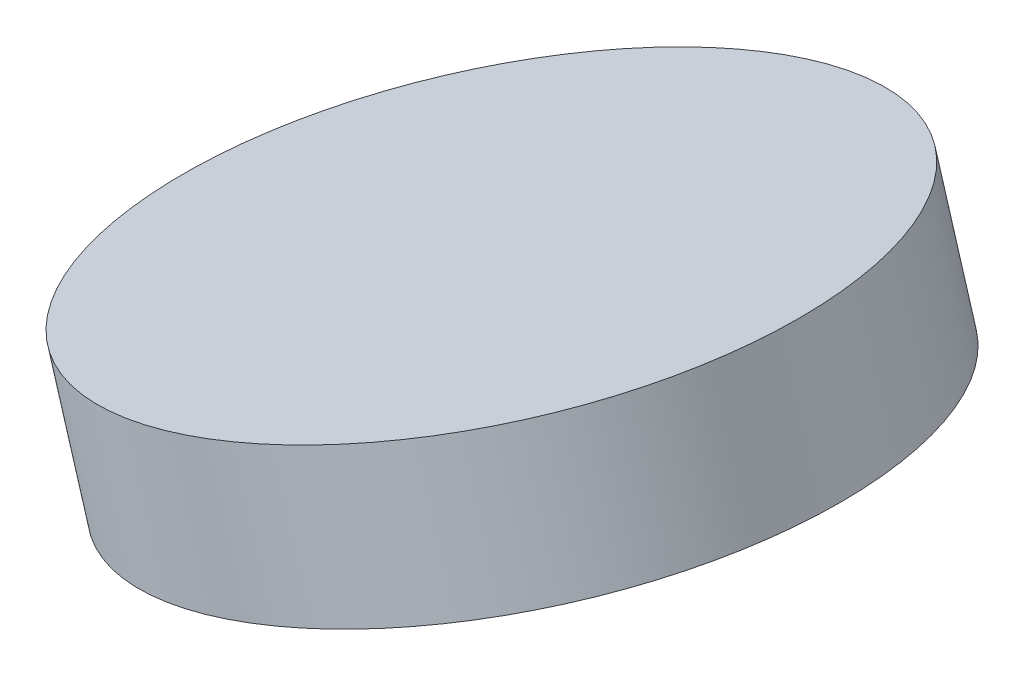
SolidWorks part; units mm, degrees
ref_plane "Front Plane" through (0, 0, 0) normal (0, 0, 1) x (1, 0, 0)
ref_plane "Top Plane" through (0, 0, 0) normal (0, 1, 0) x (1, 0, 0)
ref_plane "Right Plane" through (0, 0, 0) normal (1, 0, 0) x (0, 0, -1)
sketch "Sketch1" plane through (-3.424, 11.5011, 0) normal (0.2853, -0.9584, 0) x (-0.9186, -0.2735, -0.2853)
  circle A1 centre (0, 0) radius 4.4404
  dimension "D1" = 8.8807
extrude "Boss-Extrude1" add sketch "Sketch1" along normal blind 2
